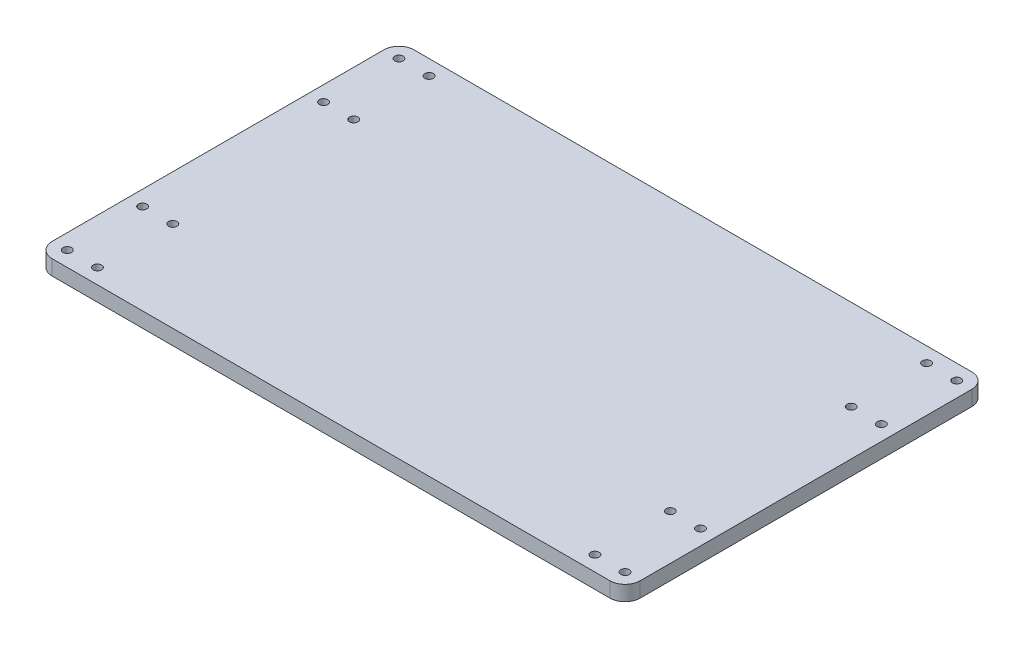
SolidWorks part; units mm, degrees
material "Pine"
ref_plane "Front Plane" through (0, 0, 0) normal (0, 0, 1) x (1, 0, 0)
ref_plane "Top Plane" through (0, 0, 0) normal (0, 1, 0) x (1, 0, 0)
ref_plane "Right Plane" through (0, 0, 0) normal (1, 0, 0) x (0, 0, -1)
sketch "Sketch1" plane through (0, 0, 0) normal (0, 1, 0) x (1, 0, 0)
  line L1 (-123.825, -76.2) -> (123.825, -76.2)
  line L2 (-123.825, -76.2) -> (-123.825, 76.2)
  line L3 (-123.825, 76.2) -> (123.825, 76.2)
  line L4 (123.825, -76.2) -> (123.825, 76.2)
  line L5 (-123.825, -76.2) -> (123.825, 76.2) construction
  line L6 (-123.825, 76.2) -> (123.825, -76.2) construction
  point P0 (0, 0)
  dimension "D1" = 152.4
  dimension "D2" = 247.65
extrude "Boss-Extrude1" add sketch "Sketch1" along normal blind 6.35
fillet "Fillet1" radius 6.35 4 edges at (-123.825, 3.175, -76.2) (123.825, 3.175, -76.2) (123.825, 3.175, 76.2) (-123.825, 3.175, 76.2)
sketch "Sketch2" plane through (0, 6.35, 0) normal (0, 1, 0) x (1, 0, 0)
  circle A0 centre (117.475, -69.85) radius 1.778
  circle A1 centre (104.775, -69.85) radius 1.778
  circle A2 centre (117.475, -38.1) radius 1.778
  circle A3 centre (104.775, -38.1) radius 1.778
  arc A5 (117.475, -76.2) -> (123.825, -69.85) centre (117.475, -69.85) ccw construction
  point P8 (0, 0)
  point P9 (0, 0)
  point P10 (0, 0)
  point P11 (116.842, -39.8934)
  point P12 (0, 0)
  point P13 (0, 0)
  point P14 (0, 0)
  point P15 (123.1171, -43.6142)
  point P16 (117.7932, -71.3865)
  point P20 (0, 0)
  point P21 (0, 0)
  dimension "D3" = 3.556
  dimension "D1" = 31.75
  dimension "D2" = 12.7
extrude "Cut-Extrude1" cut sketch "Sketch2" against normal through all
pattern_linear "LPattern1" count 2 spacing 222.25 along (-1, 0, 0) count 2 spacing 107.95 along (0, 0, -1) of "Cut-Extrude1"
